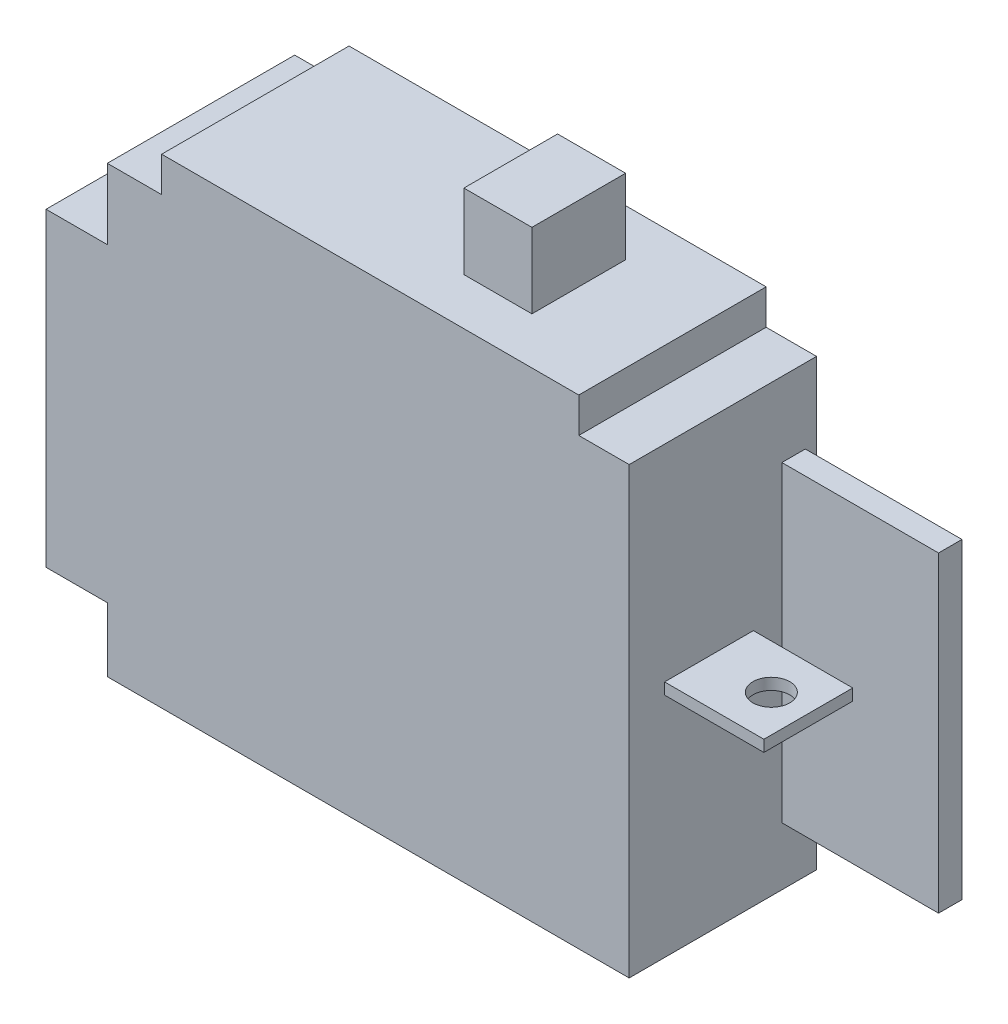
SolidWorks part; units mm, degrees
ref_plane "Front Plane" through (0, 0, 0) normal (0, 0, 1) x (1, 0, 0)
ref_plane "Top Plane" through (0, 0, 0) normal (0, 1, 0) x (1, 0, 0)
ref_plane "Right Plane" through (0, 0, 0) normal (1, 0, 0) x (0, 0, -1)
sketch "Sketch1" plane through (0, 0, 0) normal (0, 0, 1) x (1, 0, 0)
  line L0 (28.5369, 30.1371) -> (35.3695, 30.1371)
  line L1 (-35.3695, -30.1371) -> (35.3695, -30.1371)
  line L2 (-35.3695, -30.1371) -> (-35.3695, -21.4503)
  line L3 (-35.3695, 30.1371) -> (-28.0035, 30.1371)
  line L4 (35.3695, -30.1371) -> (35.3695, 30.1371)
  line L5 (-35.3695, -30.1371) -> (35.3695, 30.1371) construction
  line L6 (-35.3695, 30.1371) -> (35.3695, -30.1371) construction
  line L7 (-35.3695, -21.4503) -> (-43.6753, -21.4503)
  line L8 (-43.6753, -21.4503) -> (-43.6753, 20.5867)
  line L9 (-43.6753, 20.5867) -> (-35.3695, 20.5867)
  line L10 (-35.3695, 20.5867) -> (-35.3695, 30.1371)
  line L11 (-28.0035, 30.1371) -> (-28.0035, 34.8869)
  line L13 (28.5369, 34.8869) -> (28.5369, 30.1371)
  line L14 (28.5369, 34.8869) -> (15.8369, 34.8869)
  line L15 (15.8369, 34.8869) -> (15.8369, 45.0469)
  line L16 (15.8369, 45.0469) -> (6.6167, 45.0469)
  line L17 (6.6167, 45.0469) -> (6.6167, 34.8869)
  line L18 (6.6167, 34.8869) -> (-28.0035, 34.8869)
  point P0 (0, 0)
  dimension "D1" = 70.739
extrude "Boss-Extrude1" add sketch "Sketch1" along normal blind 25.4 contours L18 L11 L3 L10 L9 L8 L7 L2 L1 L4 L0 L13 L14 L15 L16 L17
sketch "Sketch2" plane through (35.3695, 0, 0) normal (1, 0, 0) x (0, 0, -1)
  line L0 (0, 30.1371) -> (-1.524, 30.1371)
  line L1 (-25.4, 30.1371) -> (0, 30.1371) construction
  line L2 (-1.524, 30.1371) -> (-1.524, 20.0257)
  line L10 (-1.524, 20.0257) -> (-4.699, 20.0257)
  line L11 (-1.524, 20.0257) -> (-1.524, -22.2653)
  line L12 (-1.524, -22.2653) -> (-4.699, -22.2653)
  line L13 (-4.699, 20.0257) -> (-4.699, -22.2653)
extrude "Boss-Extrude2" add sketch "Sketch2" along normal blind 21.2344 contours L11 L10 L13 L12
sketch "Sketch3" plane through (35.3695, 0, 0) normal (1, 0, 0) x (0, 0, -1)
  line L0 (-25.4, 30.1371) -> (-25.4, 0.6731)
  line L1 (-25.4, -30.1371) -> (-25.4, 30.1371) construction
  line L6 (-8.5598, 2.2225) -> (-20.5994, 2.2225)
  line L7 (-8.5598, 2.2225) -> (-8.5598, 0.6731)
  line L8 (-8.5598, 0.6731) -> (-20.5994, 0.6731)
  line L9 (-20.5994, 2.2225) -> (-20.5994, 0.6731)
extrude "Boss-Extrude3" add sketch "Sketch3" along normal blind 13.462 contours L7 L6 L9 L8
sketch "Sketch4" plane through (0, 2.2225, 0) normal (0, 1, 0) x (1, 0, 0)
  circle A0 centre (43.8213, -14.5796) radius 2.4955
extrude "Cut-Extrude1" cut sketch "Sketch4" against normal blind 16.51
sketch "Sketch5" plane through (0, 0, 25.4) normal (0, 0, 1) x (1, 0, 0)
  line L1 (6.6167, 45.0469) -> (15.8369, 45.0469)
  line L2 (6.6167, 45.0469) -> (6.6167, 34.8869)
  line L3 (6.6167, 34.8869) -> (15.8369, 34.8869)
  line L4 (15.8369, 45.0469) -> (15.8369, 34.8869)
extrude "Cut-Extrude2" cut sketch "Sketch5" against normal blind 6.35
sketch "Sketch6" plane through (0, 0, 0) normal (0, 0, -1) x (-1, 0, 0)
  line L1 (-15.8369, 45.0469) -> (-6.6167, 45.0469)
  line L2 (-15.8369, 45.0469) -> (-15.8369, 34.8869)
  line L3 (-15.8369, 34.8869) -> (-6.6167, 34.8869)
  line L4 (-6.6167, 45.0469) -> (-6.6167, 34.8869)
extrude "Cut-Extrude3" cut sketch "Sketch6" against normal blind 6.35
